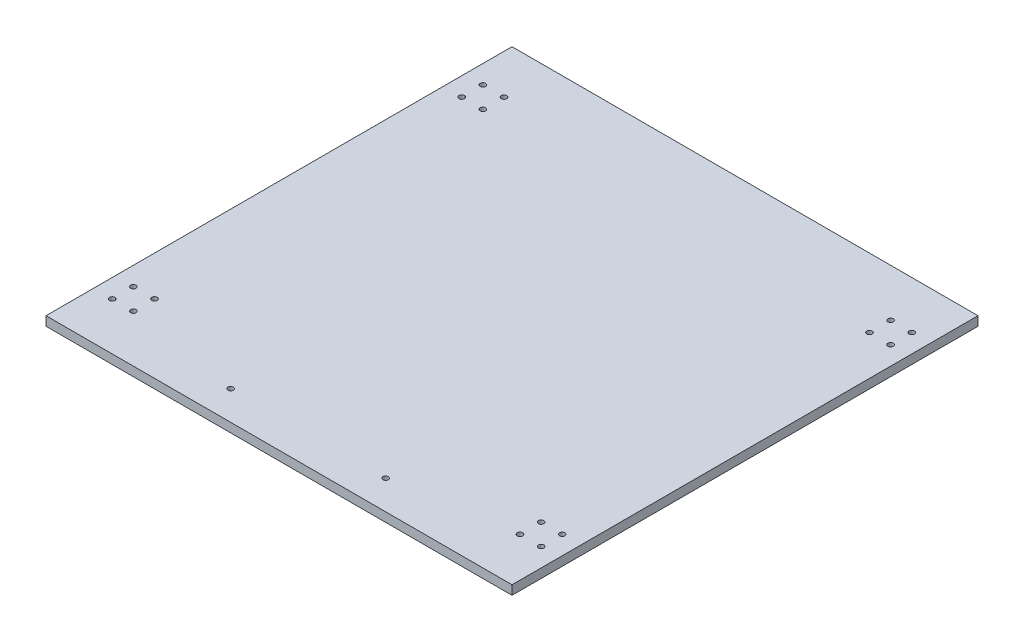
SolidWorks part; units mm, degrees
ref_plane "Front Plane" through (0, 0, 0) normal (0, 0, 1) x (1, 0, 0)
ref_plane "Top Plane" through (0, 0, 0) normal (0, 1, 0) x (1, 0, 0)
ref_plane "Right Plane" through (0, 0, 0) normal (1, 0, 0) x (0, 0, -1)
sketch "Sketch1" plane through (0, 0, 0) normal (0, 1, 0) x (1, 0, 0)
  line L0 (0, -152.4) -> (0, 152.4) construction
  line L1 (152.4, -152.4) -> (-152.4, -152.4)
  line L2 (152.4, -152.4) -> (152.4, 152.4)
  line L3 (152.4, 152.4) -> (-152.4, 152.4)
  line L4 (-152.4, -152.4) -> (-152.4, 152.4)
  line L5 (152.4, -152.4) -> (-152.4, 152.4) construction
  line L6 (152.4, 152.4) -> (-152.4, -152.4) construction
  line L7 (-133.35, -133.35) -> (133.35, -133.35) construction
  line L8 (50.69, -133.35) -> (-50.69, -133.35) construction
  line L10 (-58.6275, -141.2875) -> (-42.7525, -141.2875) construction
  line L11 (-58.6275, -141.2875) -> (-58.6275, -125.4125) construction
  line L12 (-58.6275, -125.4125) -> (-42.7525, -125.4125) construction
  line L13 (-42.7525, -141.2875) -> (-42.7525, -125.4125) construction
  line L14 (-58.6275, -141.2875) -> (-42.7525, -125.4125) construction
  line L15 (-58.6275, -125.4125) -> (-42.7525, -141.2875) construction
  line L16 (42.7525, -141.2875) -> (58.6275, -141.2875) construction
  line L17 (42.7525, -141.2875) -> (42.7525, -125.4125) construction
  line L18 (42.7525, -125.4125) -> (58.6275, -125.4125) construction
  line L19 (58.6275, -141.2875) -> (58.6275, -125.4125) construction
  line L20 (42.7525, -141.2875) -> (58.6275, -125.4125) construction
  line L21 (42.7525, -125.4125) -> (58.6275, -141.2875) construction
  line L22 (-42.7525, -141.2875) -> (42.7525, -141.2875) construction
  line L23 (-42.7525, -141.2875) -> (-42.7525, 1.5875) construction
  line L24 (-42.7525, 1.5875) -> (42.7525, 1.5875) construction
  line L25 (42.7525, -141.2875) -> (42.7525, 1.5875) construction
  circle A0 centre (-140.2648, 121.2148) radius 1.778
  circle A1 centre (-140.2648, 107.3852) radius 1.778
  circle A2 centre (-126.4352, 107.3852) radius 1.778
  circle A3 centre (-126.4352, 121.2148) radius 1.778
  circle A4 centre (-140.2648, -121.2148) radius 1.778
  circle A5 centre (-126.4352, -121.2148) radius 1.778
  circle A6 centre (-126.4352, -107.3852) radius 1.778
  circle A7 centre (-140.2648, -107.3852) radius 1.778
  circle A8 centre (126.4352, 121.2148) radius 1.764
  circle A9 centre (140.2648, 121.2148) radius 1.764
  circle A10 centre (140.2648, 107.3852) radius 1.764
  circle A11 centre (126.4352, 107.3852) radius 1.764
  circle A12 centre (-50.69, -133.35) radius 1.778
  circle A13 centre (126.4352, -107.3852) radius 1.778
  circle A14 centre (126.4352, -121.2148) radius 1.778
  circle A15 centre (140.2648, -121.2148) radius 1.778
  circle A16 centre (140.2648, -107.3852) radius 1.778
  circle A17 centre (50.69, -133.35) radius 1.778
  point P0 (0, 0)
  point P18 (-133.35, 114.3)
  point P28 (-133.35, -114.3)
  point P38 (133.35, 114.3)
  point P48 (133.35, -114.3)
  point P49 (0, 0)
  point P56 (0, -133.35)
  dimension "D1" = 304.8
  dimension "D2" = 4
  dimension "D3" = 4
  dimension "D4" = 4
  dimension "D5" = 4
extrude "Boss-Extrude1" add sketch "Sketch1" along normal blind 5.9944
